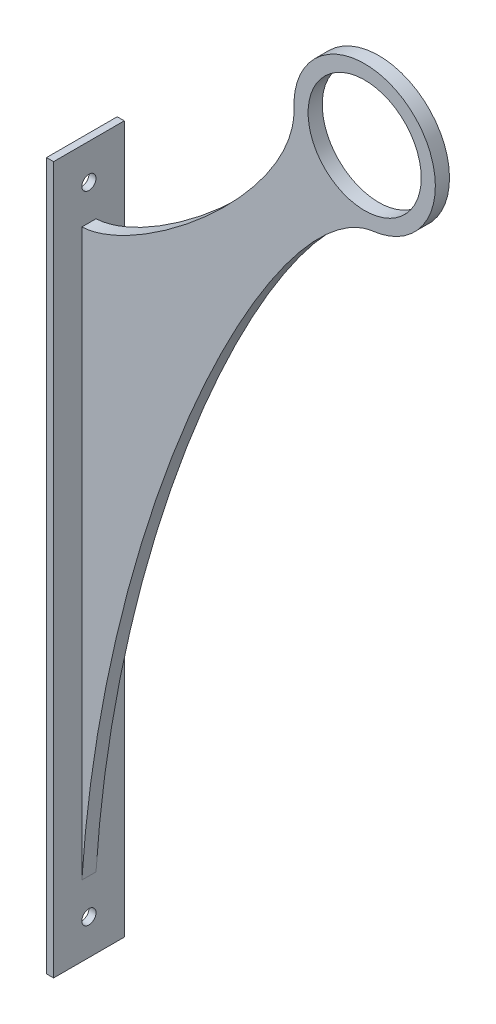
SolidWorks part; units mm, degrees
material "201 退火不锈钢 (SS)"
ref_plane "前视基准面" through (0, 0, 0) normal (0, 0, 1) x (1, 0, 0)
ref_plane "上视基准面" through (0, 0, 0) normal (0, 1, 0) x (1, 0, 0)
ref_plane "右视基准面" through (0, 0, 0) normal (1, 0, 0) x (0, 0, -1)
other "Configuration Table"
sketch "草图1" plane through (0, 0, 0) normal (1, 0, 0) x (0, 0, -1)
  line L1 (-5, -50) -> (5, -50)
  line L2 (-5, -50) -> (-5, 50)
  line L3 (-5, 50) -> (5, 50)
  line L4 (5, -50) -> (5, 50)
  line L5 (-5, -50) -> (5, 50) construction
  line L6 (-5, 50) -> (5, -50) construction
  point P0 (0, 0)
extrude "凸台-拉伸1" add sketch "草图1" along normal blind 1
sketch "草图2" plane through (1, 0, 0) normal (1, 0, 0) x (0, 0, -1)
  line L0 (-1, 40) -> (-1, 80)
  line L1 (-1, -40) -> (1, -40)
  line L2 (-1, -40) -> (-1, 40)
  line L3 (-1, 40) -> (1, 40)
  line L4 (1, -40) -> (1, 40)
  line L5 (-1, -40) -> (1, 40) construction
  line L6 (-1, 40) -> (1, -40) construction
  line L7 (-1, 80) -> (1, 80)
  line L8 (1, 80) -> (1, 40)
  point P0 (0, 0)
  line M7 (5, 50) -> (-5, 50)
extrude "凸台-拉伸3" add sketch "草图2" along normal blind 50 contours L8 L7 L0 M7 | L8 L0 L3 M7 | L1 L4 L3 L2
sketch "草图3" plane through (0, 0, 1) normal (0, 0, 1) x (1, 0, 0)
  line L0 (1, 50) -> (1, 40)
  line L1 (1, -40) -> (1, 50) construction
  line L2 (51, 80) -> (51, 70)
  line L3 (51, -40) -> (51, 80) construction
  line L4 (51, 70) -> (41, 70)
  circle A0 centre (41, 70) radius 10
  circle A1 centre (41, 70) radius 8
  spline S0 degree 3 poles (1, 40) (9.6492, 40.4235) (31.8724, 58.9217) (31, 70) knots 0 0 0 0 1 1 1 1
  spline S1 degree 3 poles (1, -40) (4.1947, 9.5031) (28.5702, 58.1745) (42.1007, 60.0608) knots 0 0 0 0 1 1 1 1
extrude "切除-拉伸11" cut sketch "草图3" against normal blind 50
sketch "草图4" plane through (0, 0, 0) normal (-1, 0, 0) x (0, 0, 1)
  line L0 (0, 50) -> (0, 44.9644)
  line L1 (-5, 50) -> (5, 50) construction
  circle A0 centre (0, 44.9644) radius 1
extrude "切除-拉伸12" cut sketch "草图4" against normal blind 1
sketch "草图5" plane through (0, 0, 0) normal (-1, 0, 0) x (0, 0, 1)
  line L0 (0, -50) -> (0, -45)
  line L1 (5, -50) -> (-5, -50) construction
  circle A0 centre (0, -45) radius 1
extrude "切除-拉伸13" cut sketch "草图5" against normal blind 1
